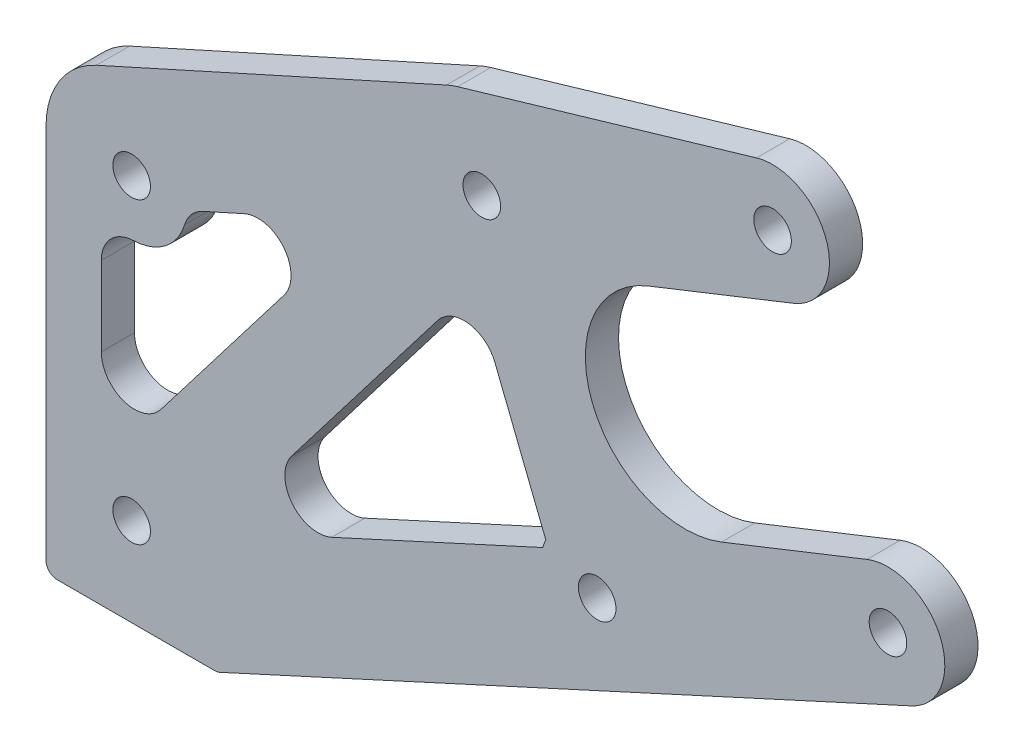
SolidWorks part; units mm, degrees
material "Thornel VCB-20 Carbon Cloth"
ref_plane "Front Plane" through (0, 0, 0) normal (0, 0, 1) x (1, 0, 0)
ref_plane "Top Plane" through (0, 0, 0) normal (0, 1, 0) x (1, 0, 0)
ref_plane "Right Plane" through (0, 0, 0) normal (1, 0, 0) x (0, 0, -1)
sketch "Sketch1" plane through (0, 0, 0) normal (0, 0, 1) x (1, 0, 0)
  line L0 (0, 0) -> (0, 27) construction
  line L1 (-7.745, -8) -> (7.745, -8)
  line L2 (0, 0) -> (0, -8) construction
  line L3 (0, 13.5) -> (50.0175, 33.3497) construction
  line L4 (50.0175, 33.3497) -> (57.9457, 51.7112) construction
  line L5 (7.745, -8) -> (70.5199, 20.7462)
  line L6 (53.3373, 24.9844) -> (66.4822, 30.201)
  line L7 (46.6977, 41.7151) -> (59.8425, 46.9317)
  line L8 (29.4737, 48.7092) -> (56.4968, 56.645)
  line L9 (-3.1843, 34.0601) -> (28.4717, 48.3381)
  line L10 (-7.745, -8) -> (-7.745, 27)
  circle A0 centre (50.0175, 33.3497) radius 20 construction
  arc A1 (53.3373, 24.9844) -> (46.6977, 41.7151) centre (50.0175, 33.3497) cw
  arc A2 (66.4822, 30.201) -> (70.5199, 20.7462) centre (68.3789, 25.4215) cw
  arc A3 (59.8425, 46.9317) -> (56.4968, 56.645) centre (57.9457, 51.7112) ccw
  arc A4 (29.4737, 48.7092) -> (28.4717, 48.3381) centre (31.656, 41.278) ccw
  arc A5 (-7.745, 27) -> (-3.1843, 34.0601) centre (0, 27) cw
  point P9 (57.9457, 51.7112)
  point P14 (31.656, 41.278)
  point P15 (42.0892, 14.9883)
  point P16 (68.3789, 25.4215)
  point P17 (50.0175, 33.3497)
  dimension "D4" = 40
  dimension "D5" = 60.1162
  dimension "D9" = 9
  dimension "D1" = 27
  dimension "D2" = 15.49
  dimension "D3" = 8
  dimension "D6" = 50.4189
  dimension "D7" = 135
  dimension "D8" = 4
extrude "Boss-Extrude1" add sketch "Sketch1" along normal blind 3
sketch "Sketch2" plane through (0, 0, 0) normal (0, 0, 1) x (1, 0, 0)
  point P0 (57.9457, 51.7112)
  point P2 (68.3789, 25.4215)
  point P4 (42.0892, 14.9883)
  point P6 (31.656, 41.278)
  point P8 (0, 27)
  point P10 (0, 0)
hole_wizard "M3 Clearance Hole1" positions "Sketch2" profile "Sketch3" hole size "M3" standard "ANSI Metric" end condition through all
sketch "Sketch3" plane through (57.9457, 51.7112, 0) normal (1, 0, 0) x (0, 1, 0)
  line L0 (0, 0) -> (0, 3)
  line L1 (0, 3) -> (1.7, 3)
  line L2 (1.7, 3) -> (1.7, 0)
  line L5 (1.7, 0) -> (0, 0)
  line L11 (0, -6.35) -> (0, 107.95) construction
  dimension "Thru Hole Dia." = 3.4
  dimension "Thru Hole Depth" = 3
fillet "Fillet1" radius 1 2 edges at (7.745, -8, 1.5) (-7.745, -8, 1.5)
sketch "Sketch4" plane through (0, 0, 0) normal (0, 0, -1) x (-1, 0, 0)
  line L0 (-31.656, 41.278) -> (0, 0) construction
  line L1 (0, 0) -> (-42.0892, 14.9883) construction
  line L2 (-42.0892, 14.9883) -> (-31.656, 41.278) construction
  line L3 (-31.656, 41.278) -> (0, 27) construction
  line L4 (0, 27) -> (0, 0) construction
  line L5 (-37.3397, 16.5508) -> (-7.1215, 2.7131)
  line L6 (-7.9433, -7.9092) -> (-70.5199, 20.7462) construction
  line L7 (-7.1215, 2.7131) -> (-30.8936, 33.7107)
  line L8 (-30.8936, 33.7107) -> (-37.5189, 17.0161)
  line L9 (2.745, 2.9937) -> (-21.0492, 34.0201)
  line L10 (2.745, 2.9937) -> (2.745, 22.8209)
  line L11 (7.745, 27) -> (7.745, -7) construction
  line L12 (-21.0492, 34.0201) -> (-4.9951, 26.7792)
  line L13 (-28.4717, 48.3381) -> (3.1843, 34.0601) construction
  line L14 (-61.925, 22.7073) -> (-48.5516, 17.4)
  line L15 (-61.8201, 22.9715) -> (-55.1817, 20.337)
  line L16 (-66.4822, 30.201) -> (-53.3373, 24.9844) construction
  line L17 (-68.3789, 25.4215) -> (-42.0892, 14.9883) construction
  line L18 (-68.3789, 25.4215) -> (-57.9457, 51.7112) construction
  line L19 (-50.0175, 33.3497) -> (-63.1623, 38.5663) construction
  line L20 (-57.9457, 51.7112) -> (-31.656, 41.278) construction
  line L22 (-51.3869, 49.2612) -> (-38.0135, 43.9539)
  line L23 (-51.4918, 48.997) -> (-44.8533, 46.3625)
  arc A0 (-37.5189, 17.0161) -> (-37.3397, 16.5508) centre (-42.0892, 14.9883) cw
  arc A3 (2.745, 22.8209) -> (-4.9951, 26.7792) centre (0, 27) cw
  arc A5 (-53.3373, 24.9844) -> (-46.6977, 41.7151) centre (-50.0175, 33.3497) ccw construction
  arc A6 (-53.3373, 24.9844) -> (-46.6977, 41.7151) centre (-50.0175, 33.3497) ccw construction
  arc A8 (-46.2108, 18.063) -> (-46.9306, 16.7211) centre (-42.0892, 14.9883) cw
  arc A9 (-66.4822, 30.201) -> (-70.5199, 20.7462) centre (-68.3789, 25.4215) ccw construction
  arc A11 (-46.2108, 18.063) -> (-48.5516, 17.4) centre (-47.8139, 19.2589) cw
  arc A16 (-36.7644, 41.8662) -> (-38.0135, 43.9539) centre (-38.7513, 42.0949) ccw
  arc A18 (-36.7644, 41.8662) -> (-36.3681, 43.3365) centre (-31.656, 41.278) ccw
  arc A20 (-55.1817, 20.337) -> (-48.9641, 19.3894) centre (-50.0175, 33.3497) ccw
  arc A22 (-46.9306, 16.7211) -> (-48.9641, 19.3894) centre (-48.8136, 17.3951) ccw
  arc A23 (-61.8201, 22.9715) -> (-61.925, 22.7073) centre (-61.8726, 22.8394) ccw
  circle A24 centre (-68.3789, 25.4215) radius 1.7 construction
  arc A25 (-36.3681, 43.3365) -> (-39.678, 42.7887) centre (-38.2009, 44.1371) cw
  arc A26 (-44.8533, 46.3625) -> (-39.678, 42.7887) centre (-50.0175, 33.3497) cw
  arc A27 (-51.4918, 48.997) -> (-51.3869, 49.2612) centre (-51.4394, 49.1291) cw
  dimension "D1" = 5
  dimension "D8" = 7
  dimension "D9" = 2
  dimension "D10" = 2
  dimension "D2" = 10
  dimension "D3" = 5
  dimension "D4" = 10
  dimension "D5" = 8
  dimension "D6" = 3.5
  dimension "D7" = 5
extrude "Cut-Extrude1" cut sketch "Sketch4" against normal through all contours L8 A0 L5 L7 | L10 A3 L12 L9 | A27 L22 A16 A18 A25 A26 L23 | A23 L14 A11 A8 A22 A20 L15
fillet "Fillet2" radius 3 6 edges at (-2.745, 22.8209, 1.5) (4.9951, 26.7792, 1.5) (-2.745, 2.9937, 1.5) (21.0492, 34.0201, 1.5) (30.8936, 33.7107, 1.5) (7.1215, 2.7131, 1.5)
